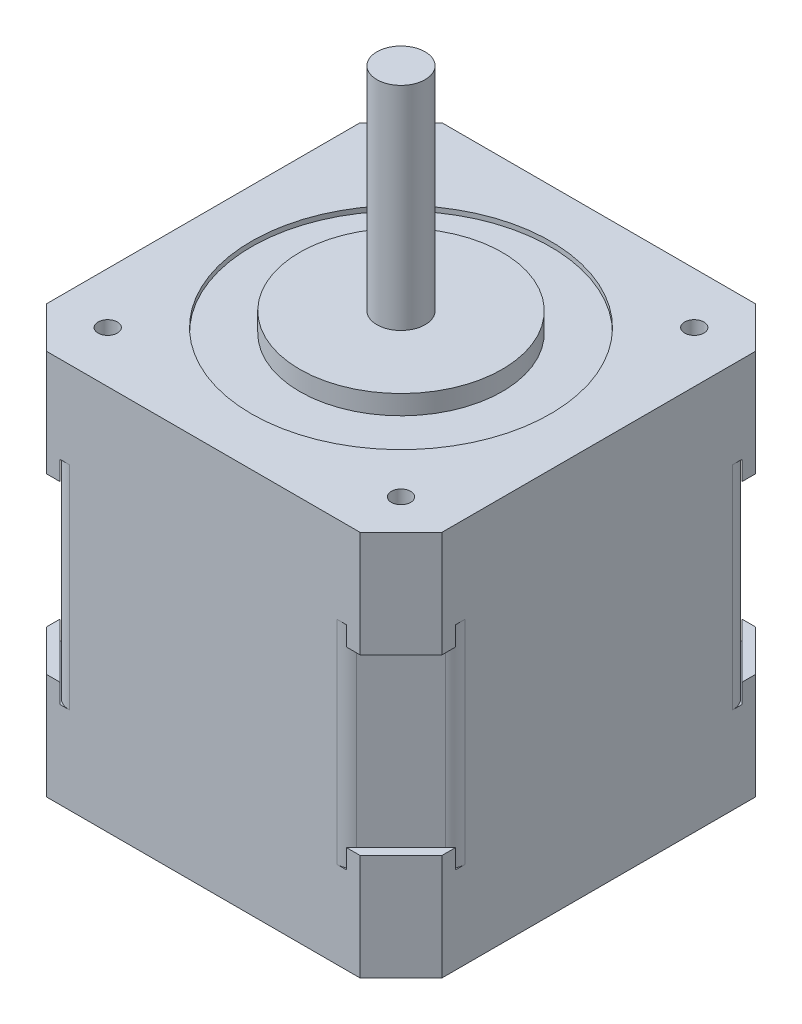
SolidWorks part; units mm, degrees
ref_plane "Front Plane" through (0, 0, 0) normal (0, 0, 1) x (1, 0, 0)
ref_plane "Top Plane" through (0, 0, 0) normal (0, 1, 0) x (1, 0, 0)
ref_plane "Right Plane" through (0, 0, 0) normal (1, 0, 0) x (0, 0, -1)
sketch "Sketch1" plane through (0, 0, 0) normal (0, 1, 0) x (1, 0, 0)
  line L0 (-20.5, -16.2574) -> (-16.2574, -20.5)
  line L1 (-16.2574, -20.5) -> (16.2574, -20.5)
  line L2 (-20.5, -16.2574) -> (-20.5, 16.2574)
  line L3 (-16.2574, 20.5) -> (16.2574, 20.5)
  line L4 (20.5, -16.2574) -> (20.5, 16.2574)
  line L5 (-18.3787, -18.3787) -> (18.3787, 18.3787) construction
  line L6 (-18.3787, 18.3787) -> (18.3787, -18.3787) construction
  line L7 (16.2574, 20.5) -> (20.5, 16.2574)
  line L8 (-20.5, 16.2574) -> (-16.2574, 20.5)
  line L9 (16.2574, -20.5) -> (20.5, -16.2574)
  point P0 (0, 0)
  dimension "D3" = 6
  dimension "D4" = 6
extrude "Boss-Extrude1" add sketch "Sketch1" along normal blind 9
sketch "Sketch2" plane through (0, 9, 0) normal (0, 1, 0) x (1, 0, 0)
  line L0 (-18.3787, -18.3787) -> (18.3787, 18.3787) construction
  line L1 (-20.5, -16.2574) -> (-16.2574, -20.5) construction
  line L2 (20.5, 16.2574) -> (16.2574, 20.5) construction
  line L3 (18.3787, 18.3787) -> (18.3787, -18.3787) construction
  line L4 (16.2574, -20.5) -> (20.5, -16.2574) construction
  line L5 (18.3787, -18.3787) -> (-18.3787, 18.3787) construction
  line L6 (-16.2574, 20.5) -> (-20.5, 16.2574) construction
  line L7 (-20.5, -14.8431) -> (-14.8431, -20.5)
  line L8 (-20.5, 16.2574) -> (-20.5, -16.2574) construction
  line L9 (-16.2574, -20.5) -> (16.2574, -20.5) construction
  line L10 (14.8431, 20.5) -> (20.5, 14.8431)
  line L11 (-20.5, 14.8431) -> (-14.8431, 20.5)
  line L12 (16.2574, 20.5) -> (-16.2574, 20.5) construction
  line L13 (14.8431, -20.5) -> (20.5, -14.8431)
  line L14 (14.8431, -20.5) -> (16.2574, -20.5)
  line L15 (16.2574, -20.5) -> (20.5, -16.2574)
  line L16 (20.5, -16.2574) -> (20.5, -14.8431)
  line L17 (20.5, 16.2574) -> (20.5, 14.8431)
  line L18 (14.8431, 20.5) -> (16.2574, 20.5)
  line L19 (16.2574, 20.5) -> (20.5, 16.2574)
  line L20 (-20.5, 14.8431) -> (-20.5, 16.2574)
  line L21 (-20.5, 16.2574) -> (-16.2574, 20.5)
  line L22 (-16.2574, 20.5) -> (-14.8431, 20.5)
  line L23 (-20.5, -14.8431) -> (-20.5, -16.2574)
  line L24 (-20.5, -16.2574) -> (-16.2574, -20.5)
  line L25 (-16.2574, -20.5) -> (-14.8431, -20.5)
  dimension "D1" = 8
  dimension "D2" = 8
extrude "Boss-Extrude2" add sketch "Sketch2" along normal blind 2
sketch "Sketch3" plane through (0, 9, 0) normal (0, 1, 0) x (1, 0, 0)
  line L0 (-14.7017, -20.5) -> (-20.5, -14.7017)
  line L1 (-14.8431, -20.5) -> (14.8431, -20.5) construction
  line L2 (-20.5, 14.8431) -> (-20.5, -14.8431) construction
  line L3 (-14.8431, -20.5) -> (-20.5, -14.8431) construction
  line L4 (-20.5, 14.7017) -> (-14.7017, 20.5)
  line L5 (14.8431, 20.5) -> (-14.8431, 20.5) construction
  line L6 (14.7017, 20.5) -> (20.5, 14.7017)
  line L7 (20.5, -14.8431) -> (20.5, 14.8431) construction
  line L8 (14.7017, -20.5) -> (20.5, -14.7017)
  line L9 (-20.5, 14.8431) -> (-14.8431, 20.5) construction
  line L10 (-14.7017, -20.5) -> (14.7017, -20.5)
  line L11 (20.5, -14.7017) -> (20.5, 14.7017)
  line L12 (20.5, -14.8431) -> (14.8431, -20.5) construction
  line L13 (14.8431, 20.5) -> (20.5, 14.8431) construction
  line L14 (14.7017, 20.5) -> (-14.7017, 20.5)
  line L15 (-20.5, 14.7017) -> (-20.5, -14.7017)
  dimension "D1" = 0.1
  dimension "D2" = 0.1
  dimension "D3" = 0.1
  dimension "D4" = 0.1
extrude "Boss-Extrude3" add sketch "Sketch3" along normal blind 11
fillet "Fillet1" radius 2 8 edges at (14.7017, 14.5, 20.5) (-20.5, 14.5, 14.7017) (-14.7017, 14.5, 20.5) (-14.7017, 14.5, -20.5) (-20.5, 14.5, -14.7017) (14.7017, 14.5, -20.5) (20.5, 14.5, -14.7017) (20.5, 14.5, 14.7017)
ref_plane "Plane1" through (0, 20, 0) normal (0, 1, 0) x (1, 0, 0)
mirror "Mirror3" of "Fillet1", "Boss-Extrude3", "Boss-Extrude2", "Boss-Extrude1"
sketch "Sketch4" plane through (0, 40, 0) normal (0, 1, 0) x (1, 0, 0)
  line L0 (20.5, 0) -> (-20.5, 0) construction
  line L1 (20.5, -16.2574) -> (20.5, 16.2574) construction
  line L2 (-20.5, 16.2574) -> (-20.5, -16.2574) construction
  circle A0 centre (0, 0) radius 15.5
  dimension "D1" = 31
extrude "Cut-Extrude1" cut sketch "Sketch4" against normal blind 0.5
sketch "Sketch6" plane through (0, 39.5, 0) normal (0, 1, 0) x (1, 0, 0)
  circle A0 centre (0, 0) radius 10.5
  dimension "D1" = 21
extrude "Boss-Extrude4" add sketch "Sketch6" along normal blind 2
sketch "Sketch7" plane through (0, 41.5, 0) normal (0, 1, 0) x (1, 0, 0)
  circle A0 centre (0, 0) radius 2.5
  dimension "D1" = 5
extrude "Boss-Extrude5" add sketch "Sketch7" along normal blind 22
sketch "Sketch8" plane through (0, 40, 0) normal (0, 1, 0) x (1, 0, 0)
  line L0 (18.3787, 18.3787) -> (-18.3787, -18.3787) construction
  line L1 (20.5, 16.2574) -> (16.2574, 20.5) construction
  line L2 (-20.5, -16.2574) -> (-16.2574, -20.5) construction
  line L3 (-18.3787, -18.3787) -> (18.3787, -18.3787) construction
  line L4 (16.2574, -20.5) -> (20.5, -16.2574) construction
  line L5 (18.3787, -18.3787) -> (-18.3787, 18.3787) construction
  line L6 (-16.2574, 20.5) -> (-20.5, 16.2574) construction
  circle A0 centre (15.1967, 15.1967) radius 1
  circle A1 centre (15.1967, -15.1967) radius 1
  circle A2 centre (-15.1967, -15.1967) radius 1
  circle A3 centre (-15.1967, 15.1967) radius 1
  dimension "D1" = 2
  dimension "D2" = 4.5
  dimension "D3" = 4.5
  dimension "D4" = 4.5
  dimension "D5" = 4.5
extrude "Cut-Extrude2" cut sketch "Sketch8" against normal blind 10
